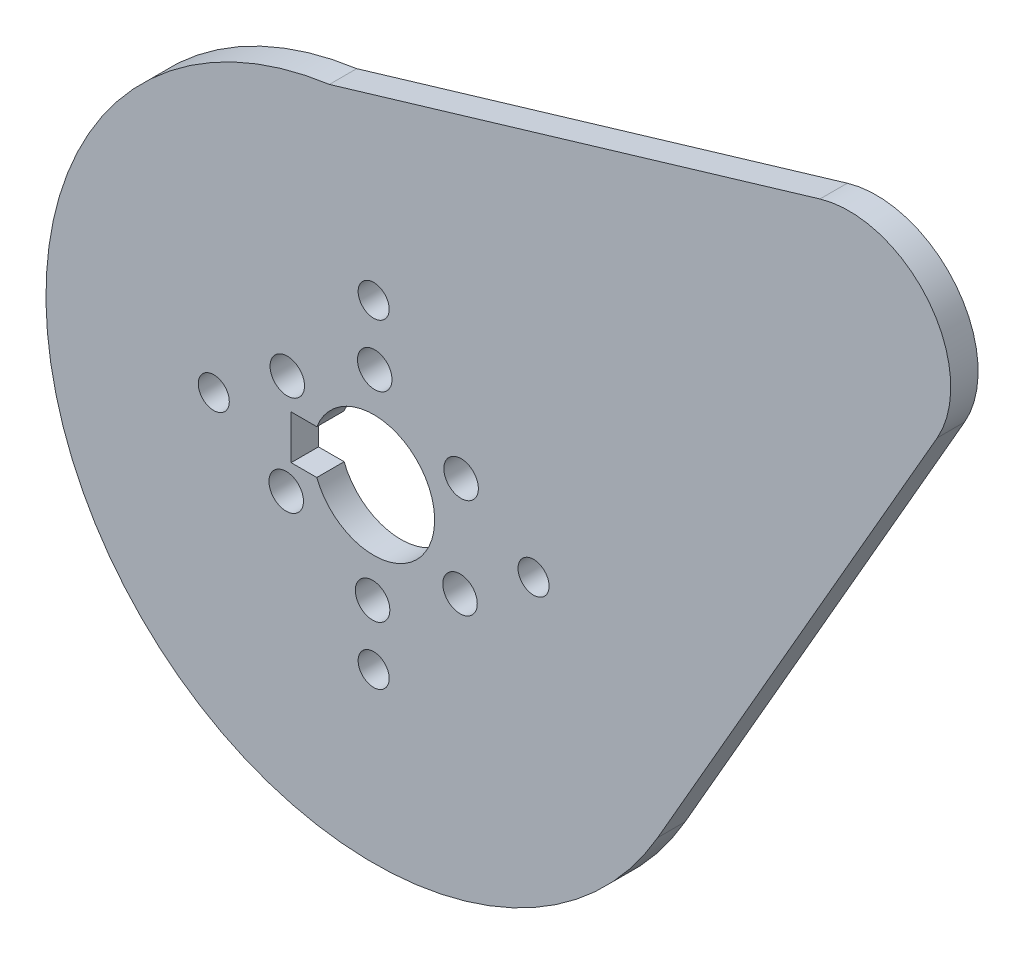
SolidWorks part; units mm, degrees
material "AISI 316 Stainless Steel Sheet (SS)"
ref_plane "Front Plane" through (0, 0, 0) normal (0, 0, 1) x (1, 0, 0)
ref_plane "Top Plane" through (0, 0, 0) normal (0, 1, 0) x (1, 0, 0)
ref_plane "Right Plane" through (0, 0, 0) normal (1, 0, 0) x (0, 0, -1)
sketch "Sketch1" plane through (0, 0, 0) normal (0, 0, 1) x (1, 0, 0)
  line L3 (32.94, -18.9461) -> (65.3479, 37.3986)
  line L4 (51.7515, 54.5911) -> (-5.1343, 37.6515)
  circle A0 centre (0, 0) radius 38
  circle A1 centre (0, 0) radius 7.07
  arc A2 (65.3479, 37.3986) -> (51.7515, 54.5911) centre (55.1191, 43.2819) ccw
  dimension "D1" = 76
  dimension "D2" = 14.14
  dimension "D8" = 11.8
  dimension "D6" = 32.94
  dimension "D7" = 65
extrude "Boss-Extrude2" add sketch "Sketch1" along normal blind 3.17
sketch "Sketch2" plane through (0, 0, 3.17) normal (0, 0, 1) x (1, 0, 0)
  circle A0 centre (-18.54, 0) radius 1.7998
  dimension "D1" = 18.54
extrude "Cut-Extrude1" cut sketch "Sketch2" against normal blind 3.17
pattern_circular "CirPattern1" count 4 over 360 about axis through (0, 0, 0) along (0, 0, 1) of "Cut-Extrude1"
hole_wizard "Ø4.0mm Dowel Hole1" positions "Sketch3" profile "Sketch4" hole size "Ø4.0" standard "ANSI Metric" end condition through all
sketch "Sketch3" plane through (0, 0, 3.17) normal (0, 0, 1) x (1, 0, 0)
  point P0 (-10.14, -5.71)
  dimension "D1" = 10.14
  dimension "D2" = 5.71
sketch "Sketch4" plane through (-10.14, -5.71, 3.17) normal (1, 0, 0) x (0, -1, 0)
  line L0 (0, 0) -> (0, 3.17)
  line L1 (0, 3.17) -> (2, 3.17)
  line L2 (2, 3.17) -> (2, 0)
  line L5 (2, 0) -> (0, 0)
  line L11 (0, -6.35) -> (0, 107.95) construction
  dimension "Thru Hole Dia." = 4
  dimension "Thru Hole Depth" = 3.17
pattern_circular "CirPattern2" count 6 over 360 about axis through (0, 0, 0) along (0, 0, 1) of "Ø4.0mm Dowel Hole1"
sketch "Sketch5" plane through (0, 0, 0) normal (0, 0, -1) x (-1, 0, 0)
  line L1 (6.5941, 2.55) -> (9.57, 2.55)
  line L3 (6.5941, -2.55) -> (9.57, -2.55)
  line L4 (9.57, 2.55) -> (9.57, -2.55)
  line L5 (7.07, 0) -> (9.57, -2.55) construction
  line L6 (7.07, 0) -> (9.57, 2.55) construction
  circle A0 centre (0, 0) radius 7.07 construction
  arc A1 (6.5941, -2.55) -> (6.5941, 2.55) centre (0, 0) ccw
  point P0 (7.07, 0)
  point P2 (9.57, 0)
  dimension "D1" = 5.1
  dimension "D2" = 2.5
  dimension "D3" = 2.9759
extrude "Cut-Extrude2" cut sketch "Sketch5" against normal up to next
